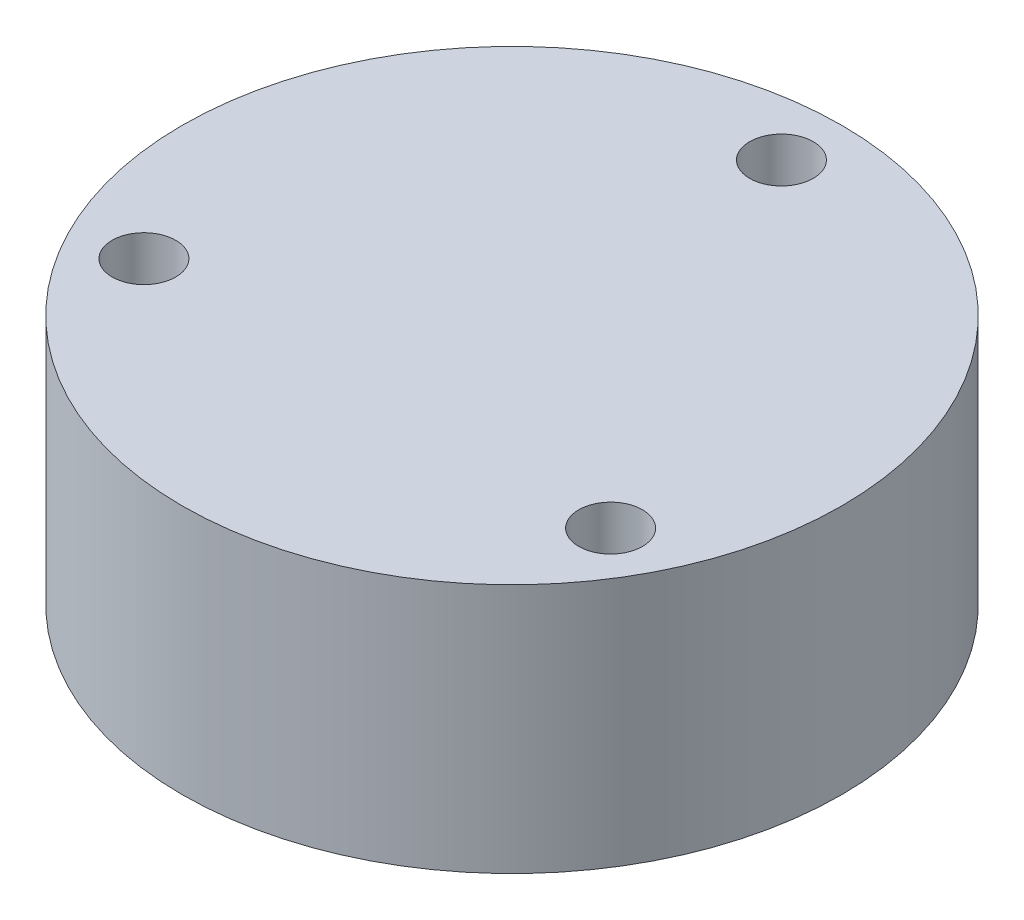
SolidWorks part; units mm, degrees
ref_plane "Front Plane" through (0, 0, 0) normal (0, 0, 1) x (1, 0, 0)
ref_plane "Top Plane" through (0, 0, 0) normal (0, 1, 0) x (1, 0, 0)
ref_plane "Right Plane" through (0, 0, 0) normal (1, 0, 0) x (0, 0, -1)
sketch "Sketch2" plane through (0, 0, 0) normal (0, 1, 0) x (1, 0, 0)
  circle A0 centre (0, 0) radius 29
  dimension "D1" = 58
extrude "Boss-Extrude1" add sketch "Sketch2" along normal blind 22
sketch "Sketch3" plane through (0, 22, 0) normal (0, 1, 0) x (1, 0, 0)
  line L0 (0, 29) -> (0, 26.5) construction
  circle A0 centre (0, 23.7) radius 2.8
  circle A1 centre (0, 0) radius 29 construction
  circle A2 centre (20.5248, -11.85) radius 2.8
  circle A3 centre (-20.5248, -11.85) radius 2.8
  point P13 (0, 0)
  dimension "D1" = 5.6
  dimension "D2" = 2.5
  dimension "D3" = 3
extrude "Cut-Extrude1" cut sketch "Sketch3" against normal through all
